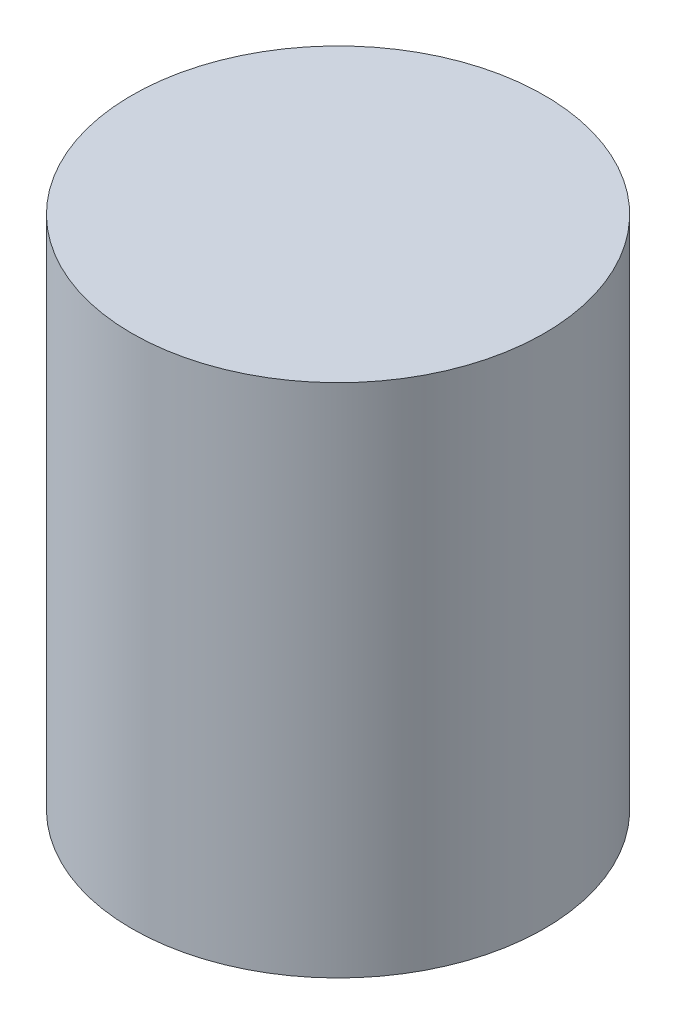
SolidWorks part; units mm, degrees
ref_plane "Front Plane" through (0, 0, 0) normal (0, 0, 1) x (1, 0, 0)
ref_plane "Top Plane" through (0, 0, 0) normal (0, 1, 0) x (1, 0, 0)
ref_plane "Right Plane" through (0, 0, 0) normal (1, 0, 0) x (0, 0, -1)
other "Configuration Table"
sketch "Sketch1" plane through (0, 0, 0) normal (0, 1, 0) x (1, 0, 0)
  circle A0 centre (350, 280) radius 20
extrude "PRESS_PZP400_piston_mili" add sketch "Sketch1" along normal blind 50 from offset 1020 separate body
